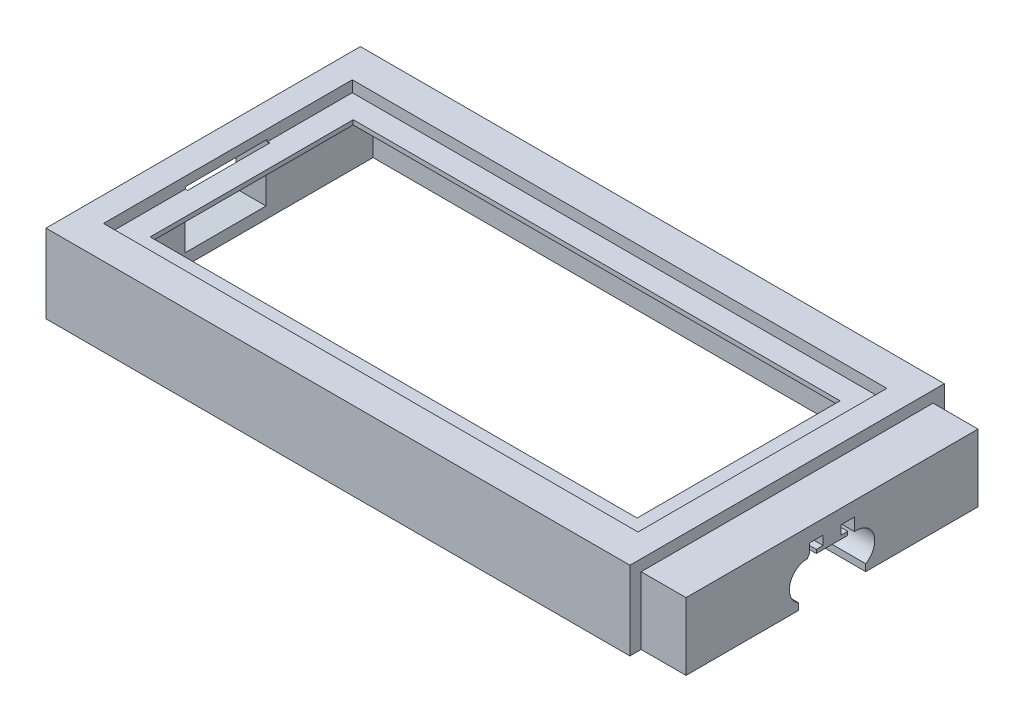
SolidWorks part; units mm, degrees
ref_plane "Front Plane" through (0, 0, 0) normal (0, 0, 1) x (1, 0, 0)
ref_plane "Top Plane" through (0, 0, 0) normal (0, 1, 0) x (1, 0, 0)
ref_plane "Right Plane" through (0, 0, 0) normal (1, 0, 0) x (0, 0, -1)
sketch "Sketch1" plane through (0, 0, 0) normal (0, 1, 0) x (1, 0, 0)
  line L1 (-82.55, -44.45) -> (82.55, -44.45)
  line L2 (-82.55, -44.45) -> (-82.55, 44.45)
  line L3 (-82.55, 44.45) -> (82.55, 44.45)
  line L4 (82.55, -44.45) -> (82.55, 44.45)
  line L5 (-82.55, -44.45) -> (82.55, 44.45) construction
  line L6 (-82.55, 44.45) -> (82.55, -44.45) construction
  point P0 (0, 0)
  dimension "D1" = 165.1
  dimension "D2" = 88.9
extrude "Boss-Extrude1" add sketch "Sketch1" along normal blind 25.4
sketch "Sketch2" plane through (82.55, 0, 0) normal (1, 0, 0) x (0, 0, -1)
  line L0 (-41.275, 3.175) -> (-41.275, 22.225)
  line L1 (-44.45, 0) -> (44.45, 0)
  line L2 (-44.45, 0) -> (-44.45, 25.4)
  line L3 (-44.45, 25.4) -> (44.45, 25.4)
  line L4 (44.45, 0) -> (44.45, 25.4)
  line L5 (-41.275, 22.225) -> (41.275, 22.225)
  line L6 (41.275, 3.175) -> (41.275, 22.225)
  line L7 (-41.275, 3.175) -> (41.275, 3.175)
  line L9 (-44.45, 25.4) -> (44.45, 25.4)
  line L10 (-44.45, 25.4) -> (-44.45, 0)
  line L11 (-44.45, 0) -> (44.45, 0)
  line L12 (44.45, 25.4) -> (44.45, 0)
  dimension "D1" = 3.175
extrude "Boss-Extrude2" add sketch "Sketch2" along normal blind 12.7 contours L0 L7 L6 L5
sketch "Sketch5" plane through (0, 25.4, 0) normal (0, 1, 0) x (1, 0, 0)
  line L1 (-75.565, -35.179) -> (75.565, -35.179)
  line L2 (-75.565, -35.179) -> (-75.565, 35.179)
  line L3 (-75.565, 35.179) -> (75.565, 35.179)
  line L4 (75.565, -35.179) -> (75.565, 35.179)
  line L5 (-75.565, -35.179) -> (75.565, 35.179) construction
  line L6 (-75.565, 35.179) -> (75.565, -35.179) construction
  point P0 (0, 0)
  dimension "D1" = 151.13
  dimension "D2" = 70.358
extrude "Cut-Extrude3" cut sketch "Sketch5" against normal blind 3.175
sketch "Sketch7" plane through (0, 0, 0) normal (0, -1, 0) x (1, 0, 0)
  line L0 (82.55, -44.45) -> (-82.55, -44.45) construction
  line L1 (-82.55, 44.45) -> (82.55, 44.45)
  line L2 (-82.55, 44.45) -> (-82.55, -44.45)
  line L3 (-82.55, -44.45) -> (82.55, -44.45)
  line L4 (82.55, 44.45) -> (82.55, -44.45)
extrude "Cut-Extrude4" cut sketch "Sketch7" against normal blind 3.175
sketch "Sketch9" plane through (95.25, 0, 0) normal (1, 0, 0) x (0, 0, -1)
  line L0 (6.985, 9.525) -> (-6.985, 9.525) construction
  line L1 (6.985, 4.445) -> (-6.985, 4.445)
  line L2 (6.985, 14.605) -> (-6.985, 14.605)
  arc A0 (6.985, 4.445) -> (6.985, 14.605) centre (6.985, 9.525) ccw
  arc A1 (-6.985, 14.605) -> (-6.985, 4.445) centre (-6.985, 9.525) ccw
  point P2 (0, 9.525)
  dimension "D1" = 13.97
extrude "Cut-Extrude5" cut sketch "Sketch9" against normal blind 29.21
sketch "Sketch11" plane through (0, 3.175, 0) normal (0, -1, 0) x (-1, 0, 0)
  line L5 (75.8025, 41.275) -> (75.8025, -41.275)
  line L6 (75.8025, -41.275) -> (-66.675, -41.275)
  line L7 (-66.675, 41.275) -> (-66.675, -41.275)
  line L8 (75.8025, 41.275) -> (-66.675, 41.275)
  line L9 (-75.565, -35.179) -> (-75.565, 35.179) construction
  dimension "D1" = 8.89
extrude "Cut-Extrude7" cut sketch "Sketch11" against normal blind 17.78 contours L7 L6 L5 L8
sketch "Sketch15" plane through (0, 22.225, 0) normal (0, 1, 0) x (1, 0, 0)
  line L6 (-68.834, 28.702) -> (-68.834, -28.702)
  line L7 (-68.834, -28.702) -> (68.834, -28.702)
  line L8 (68.834, 28.702) -> (68.834, -28.702)
  line L9 (-68.834, 28.702) -> (68.834, 28.702)
extrude "Cut-Extrude8" cut sketch "Sketch15" against normal blind 6.35
sketch "Sketch19" plane through (0, 3.175, 0) normal (0, -1, 0) x (-1, 0, 0)
  line L0 (-82.55, -41.275) -> (-82.55, -44.45) construction
  line L1 (-66.675, -41.275) -> (-79.375, -41.275)
  line L2 (-66.675, -41.275) -> (-66.675, -17.145)
  line L3 (-66.675, -17.145) -> (-79.375, -17.145)
  line L4 (-79.375, -41.275) -> (-79.375, -17.145)
  line L6 (-82.55, 44.45) -> (-82.55, 41.275) construction
  line L7 (-66.675, 41.275) -> (-79.375, 41.275)
  line L8 (-66.675, 41.275) -> (-66.675, 17.145)
  line L9 (-66.675, 17.145) -> (-79.375, 17.145)
  line L10 (-79.375, 41.275) -> (-79.375, 17.145)
  point P16 (-82.55, 42.8625)
  dimension "D1" = 3.175
  dimension "D3" = 3.175
extrude "Cut-Extrude9" cut sketch "Sketch19" against normal blind 17.78
sketch "Sketch22" plane through (-82.55, 0, 0) normal (-1, 0, 0) x (0, 0, 1)
  line L0 (44.45, 3.175) -> (-44.45, 3.175) construction
  line L1 (10.097, 8.255) -> (-9.207, 8.255)
  line L2 (10.097, 8.255) -> (10.097, 20.955)
  line L3 (10.097, 20.955) -> (-9.207, 20.955)
  line L4 (-9.207, 8.255) -> (-9.207, 20.955)
  line L5 (10.097, 8.255) -> (-9.207, 20.955) construction
  line L6 (10.097, 20.955) -> (-9.207, 8.255) construction
  point P0 (0.445, 14.605)
  point P5 (0, 0)
  dimension "D1" = 12.7
  dimension "D2" = 19.304
  dimension "D3" = 5.08
extrude "Cut-Extrude11" cut sketch "Sketch22" against normal blind 7.62 draft 15 draft outward yes
sketch "Sketch24" plane through (0, 3.175, 0) normal (0, -1, 0) x (1, 0, 0)
  line L0 (95.25, 41.275) -> (95.25, -41.275) construction
  line L1 (95.25, -9.525) -> (66.675, -9.525)
  line L2 (95.25, -9.525) -> (95.25, 9.525)
  line L3 (95.25, 9.525) -> (66.675, 9.525)
  line L4 (66.675, -9.525) -> (66.675, 9.525)
  line L5 (66.675, -17.145) -> (66.675, 17.145) construction
  line L6 (79.375, -17.145) -> (68.834, -17.145) construction
  dimension "D1" = 19.05
  dimension "D2" = 7.62
extrude "Cut-Extrude12" cut sketch "Sketch24" against normal blind 5.08
sketch "Sketch27" plane through (95.25, 0, 0) normal (1, 0, 0) x (0, 0, -1)
  line L5 (2.54, 15.621) -> (2.54, 18.161)
  line L6 (2.54, 18.161) -> (6.35, 18.161)
  line L7 (6.35, 15.621) -> (6.35, 18.161)
  line L8 (2.54, 15.621) -> (4.445, 15.621)
  line L9 (6.985, 14.605) -> (-6.985, 14.605) construction
  line L12 (-6.985, 14.605) -> (-4.445, 14.605)
  line L14 (6.35, 15.621) -> (6.35, 14.605)
  line L15 (6.35, 14.605) -> (4.445, 14.605)
  line L16 (4.445, 15.621) -> (4.445, 14.605)
  line L17 (-4.445, 15.621) -> (-4.445, 14.605)
  line L19 (-6.35, 15.621) -> (-6.985, 14.605)
  line L20 (-2.54, 15.621) -> (-4.445, 15.621)
  line L21 (-6.35, 15.621) -> (-6.35, 18.161)
  line L22 (-2.54, 18.161) -> (-6.35, 18.161)
  line L23 (-2.54, 15.621) -> (-2.54, 18.161)
  line L25 (-6.985, 4.445) -> (6.985, 4.445)
  line L26 (6.985, 14.605) -> (-6.985, 14.605)
  line L27 (-6.985, 4.445) -> (6.985, 4.445)
  line L28 (6.985, 14.605) -> (-6.985, 14.605)
  arc A2 (-6.985, 14.605) -> (-6.985, 4.445) centre (-6.985, 9.525) ccw
  arc A3 (6.985, 4.445) -> (6.985, 14.605) centre (6.985, 9.525) ccw
  arc A4 (-6.985, 14.605) -> (-6.985, 4.445) centre (-6.985, 9.525) ccw
  arc A5 (6.985, 4.445) -> (6.985, 14.605) centre (6.985, 9.525) ccw
  line M13 (-6.985, 14.605) -> (6.985, 14.605)
  dimension "D5" = 0
extrude "Cut-Extrude14" cut sketch "Sketch27" against normal blind 30.48 contours L20 L23 L22 L21 L19 L17 M13 | L8 L16 L14 L7 L6 L5 M13
